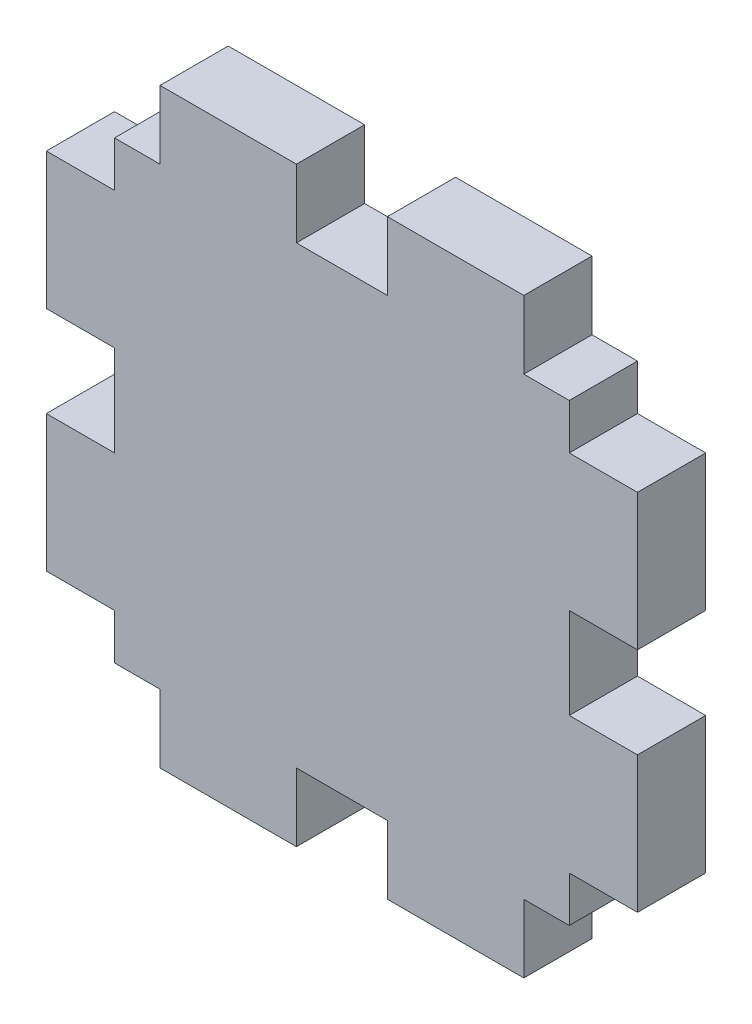
SolidWorks part; units mm, degrees
ref_plane "前视基准面" through (0, 0, 0) normal (0, 0, 1) x (1, 0, 0)
ref_plane "上视基准面" through (0, 0, 0) normal (0, 1, 0) x (1, 0, 0)
ref_plane "右视基准面" through (0, 0, 0) normal (1, 0, 0) x (0, 0, -1)
sketch "草图1" plane through (0, 0, 0) normal (0, 0, 1) x (1, 0, 0)
  line L0 (0, -55) -> (0, 55) construction
  line L1 (-10, 10) -> (-8, 10)
  line L2 (-10, 10) -> (-10, 8)
  line L3 (-10, -10) -> (-8, -10)
  line L4 (10, 10) -> (10, 8)
  line L5 (-10, 10) -> (10, -10) construction
  line L6 (-10, -10) -> (10, 10) construction
  line L11 (-5, 5) -> (5, -5) construction
  line L12 (-5, -5) -> (5, 5) construction
  line L14 (-2, 10) -> (-2, 13)
  line L15 (-2, 13) -> (-8, 13)
  line L16 (-8, 10) -> (-8, 13)
  line L17 (2, 13) -> (8, 13)
  line L18 (8, 10) -> (8, 13)
  line L20 (2, 10) -> (2, 13)
  line L21 (55, 0) -> (-55, 0) construction
  line L22 (2, -10) -> (2, -13)
  line L24 (8, -10) -> (8, -13)
  line L25 (2, -13) -> (8, -13)
  line L26 (-2, -13) -> (-8, -13)
  line L27 (-8, -10) -> (-8, -13)
  line L29 (-2, -10) -> (-2, -13)
  line L30 (10, -2) -> (13, -2)
  line L31 (10, 8) -> (13, 8)
  line L33 (10, 2) -> (13, 2)
  line L34 (13, 8) -> (13, 2)
  line L35 (13, -8) -> (13, -2)
  line L36 (10, -8) -> (13, -8)
  line L39 (-10, -8) -> (-13, -8)
  line L40 (-13, -8) -> (-13, -2)
  line L41 (-10, -2) -> (-13, -2)
  line L42 (-10, 2) -> (-13, 2)
  line L43 (-13, 8) -> (-13, 2)
  line L44 (-10, 8) -> (-13, 8)
  line L46 (-2, 10) -> (2, 10)
  line L47 (8, 10) -> (10, 10)
  line L48 (10, 2) -> (10, -2)
  line L49 (10, -8) -> (10, -10)
  line L50 (8, -10) -> (10, -10)
  line L51 (-2, -10) -> (2, -10)
  line L52 (-10, -8) -> (-10, -10)
  line L53 (-10, 2) -> (-10, -2)
  point P0 (0, 0)
  point P5 (0, 0)
  dimension "D1" = 20
  dimension "D2" = 20
  dimension "D3" = 6
  dimension "D4" = 3
  dimension "D5" = 2
  dimension "D6" = 6
  dimension "D7" = 3
  dimension "D8" = 2
extrude "凸台-拉伸1" add sketch "草图1" along normal blind 3
